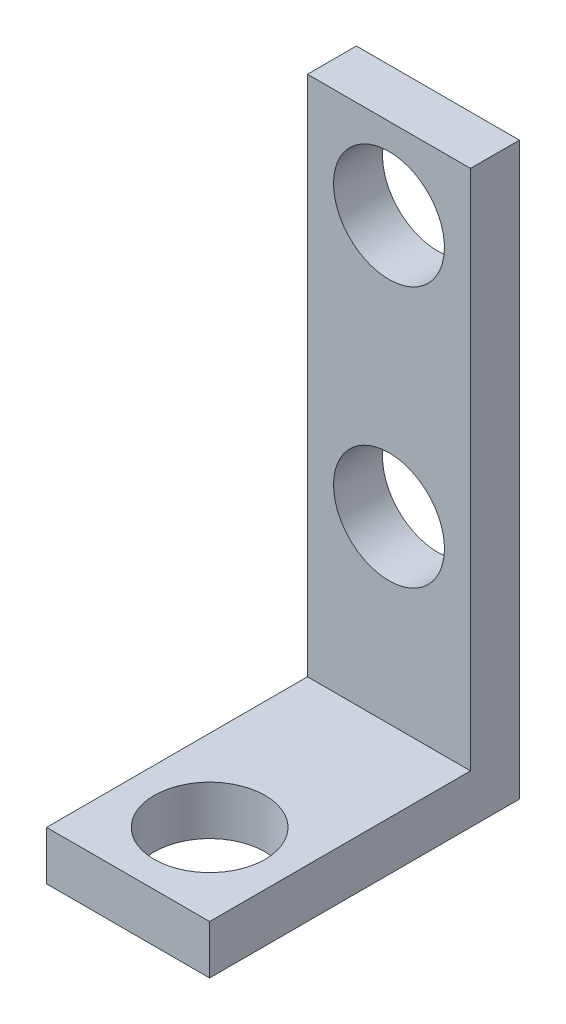
SolidWorks part; units mm, degrees
ref_plane "Front Plane" through (0, 0, 0) normal (0, 0, 1) x (1, 0, 0)
ref_plane "Top Plane" through (0, 0, 0) normal (0, 1, 0) x (1, 0, 0)
ref_plane "Right Plane" through (0, 0, 0) normal (1, 0, 0) x (0, 0, -1)
sketch "Sketch1" plane through (0, 0, 0) normal (1, 0, 0) x (0, 0, -1)
  line L1 (-4.75, -8.75) -> (4.75, -8.75)
  line L2 (-4.75, -8.75) -> (-4.75, 8.75)
  line L3 (-4.75, 8.75) -> (4.75, 8.75)
  line L4 (4.75, -8.75) -> (4.75, 8.75)
  line L5 (0, 8.75) -> (0, -8.75) construction
  line L6 (-4.75, 0) -> (4.75, 0) construction
  line L7 (-4.75, 8.75) -> (3.25, 8.75)
  line L8 (-4.75, 8.75) -> (-4.75, -7.25)
  line L9 (-4.75, -7.25) -> (3.25, -7.25)
  line L10 (3.25, 8.75) -> (3.25, -7.25)
  point P0 (0, 0)
  dimension "D1" = 9.5
  dimension "D2" = 17.5
  dimension "D3" = 1.5
  dimension "D4" = 1.5
extrude "Boss-Extrude1" add sketch "Sketch1" along normal blind 5 contours L3 L10 L9 L2 L1 L4
sketch "Sketch2" plane through (0, -8.75, 0) normal (0, -1, 0) x (1, 0, 0)
  line L0 (2.5, 4.75) -> (2.5, -4.75) construction
  line L1 (5, 4.75) -> (0, 4.75) construction
  line L2 (5, -4.75) -> (0, -4.75) construction
  circle A0 centre (2.5, 2.25) radius 1.7
  dimension "D1" = 3.4
  dimension "D2" = 7
extrude "Cut-Extrude1" cut sketch "Sketch2" against normal through all
sketch "Sketch3" plane through (0, 0, -4.75) normal (0, 0, -1) x (-1, 0, 0)
  line L0 (-2.5, 8.75) -> (-2.5, -8.75) construction
  line L1 (-5, 8.75) -> (0, 8.75) construction
  line L2 (-5, -8.75) -> (0, -8.75) construction
  circle A0 centre (-2.5, -1.75) radius 1.7
  circle A1 centre (-2.5, 6.25) radius 1.7
  dimension "D1" = 3.4
  dimension "D2" = 3.4
  dimension "D3" = 7
  dimension "D4" = 8
extrude "Cut-Extrude2" cut sketch "Sketch3" against normal through all
